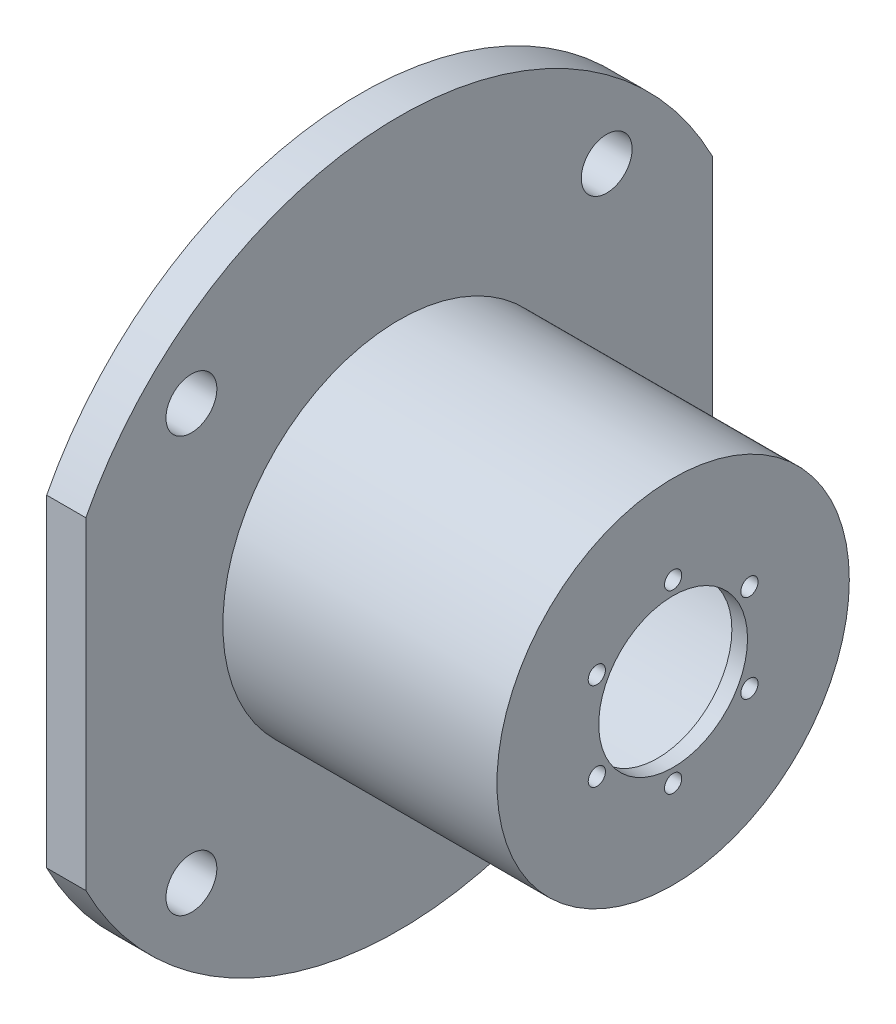
SolidWorks part; units mm, degrees
ref_plane "Płaszczyzna przednia" through (0, 0, 0) normal (0, 0, 1) x (1, 0, 0)
ref_plane "Płaszczyzna górna" through (0, 0, 0) normal (0, 1, 0) x (1, 0, 0)
ref_plane "Płaszczyzna prawa" through (0, 0, 0) normal (1, 0, 0) x (0, 0, -1)
sketch "Szkic1" plane through (0, 0, 0) normal (0, 0, 1) x (1, 0, 0)
  line L0 (0, 0) -> (-50000, 0) construction
  line L1 (-2, 9.5) -> (-2, 20)
  line L2 (-2, 20) -> (-40, 20)
  line L3 (-40, 20) -> (-40, 45)
  line L7 (-2, 9.5) -> (0, 9.5)
  line L8 (-40, 45) -> (-35, 45)
  line L9 (-35, 45) -> (-35, 22.5)
  line L10 (-35, 22.5) -> (0, 22.5)
  line L11 (0, 22.5) -> (0, 9.5)
  dimension "D2" = 40
  dimension "D3" = 90
  dimension "D4" = 2
  dimension "D5" = 19
  dimension "D6" = 40
  dimension "D1" = 5
  dimension "D7" = 45
revolve "Obrót1" add sketch "Szkic1" angle 360 about L0
sketch "Szkic2" plane through (0, 0, 0) normal (1, 0, 0) x (0, 0, -1)
  line L0 (0, 0) -> (26.5165, 26.5165) construction
  line L1 (0, 0) -> (0, 50000) construction
  line L2 (-45, -20.6155) -> (-40, -20.6155)
  line L3 (45, 20.6155) -> (40, 20.6155)
  line L4 (45, 20.6155) -> (45, -20.6155)
  line L5 (45, -20.6155) -> (40, -20.6155)
  line L6 (40, 20.6155) -> (40, -20.6155)
  line L11 (-45, 20.6155) -> (-40, 20.6155)
  line L12 (-40, 20.6155) -> (-40, -20.6155)
  line L13 (-45, 20.6155) -> (-45, -20.6155)
  circle A0 centre (0, 0) radius 11.25 construction
  circle A1 centre (0, 0) radius 37.5 construction
  circle A2 centre (26.5165, 26.5165) radius 3.25
  circle A5 centre (26.5165, -26.5165) radius 3.25
  circle A7 centre (-26.5165, -26.5165) radius 3.25
  circle A9 centre (-26.5165, 26.5165) radius 3.25
  circle A10 centre (0, 0) radius 45 construction
  circle A11 centre (0, 11.25) radius 1.1
  circle A12 centre (9.7428, 5.625) radius 1.1
  circle A13 centre (9.7428, -5.625) radius 1.1
  circle A14 centre (0, -11.25) radius 1.1
  circle A15 centre (-9.7428, -5.625) radius 1.1
  circle A16 centre (-9.7428, 5.625) radius 1.1
  point P23 (0, 0)
  point P40 (0, 0)
  dimension "D1" = 22.5
  dimension "D2" = 75
  dimension "D3" = 6.5
  dimension "D4" = 2.2
  dimension "D6" = 45
  dimension "D7" = 80
  dimension "D5" = 4
  dimension "D8" = 6
extrude "Wytnij-wyciągnięcie1" cut sketch "Szkic2" against normal through all
sketch "Szkic3" plane through (0, 0, 0) normal (0, 1, 0) x (1, 0, 0)
  line L1 (-11, 15) -> (-19, 15)
  line L2 (-11, 15) -> (-11, 22.5)
  line L3 (-11, 22.5) -> (-19, 22.5)
  line L4 (-19, 15) -> (-19, 22.5)
  line L5 (-35, -22.5) -> (-35, 22.5) construction
  line L6 (0, 22.5) -> (-35, 22.5) construction
  dimension "D1" = 8
  dimension "D2" = 7.5
  dimension "D3" = 16
extrude "Wytnij-wyciągnięcie2" [suppressed] cut sketch "Szkic3" against normal blind 20
